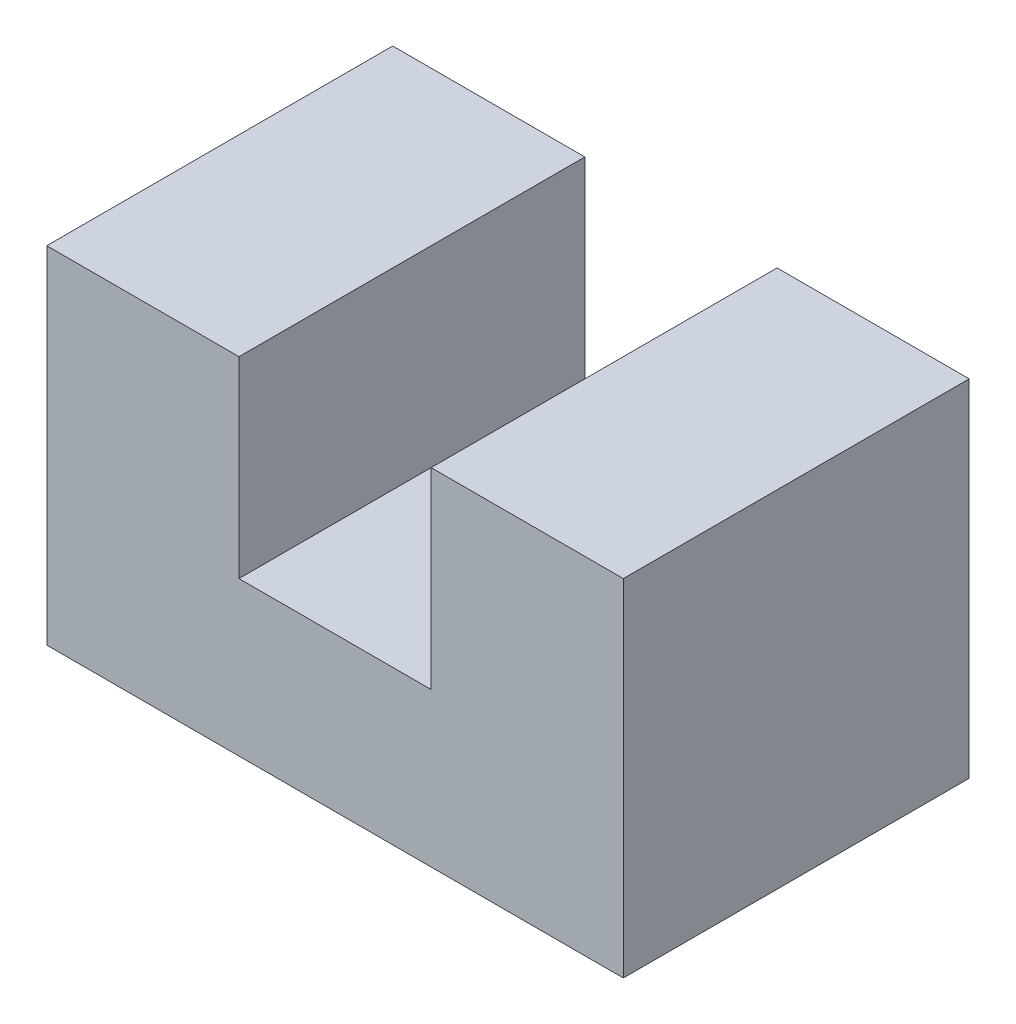
SolidWorks part; units mm, degrees
ref_plane "Front Plane" through (0, 0, 0) normal (0, 0, 1) x (1, 0, 0)
ref_plane "Top Plane" through (0, 0, 0) normal (0, 1, 0) x (1, 0, 0)
ref_plane "Right Plane" through (0, 0, 0) normal (1, 0, 0) x (0, 0, -1)
sketch "Esquisse1" plane through (0, 0, 0) normal (0, 0, 1) x (1, 0, 0)
  line L0 (0, 0) -> (100, 0)
  line L1 (100, 0) -> (100, 60)
  line L2 (100, 60) -> (66.6667, 60)
  line L3 (66.6667, 60) -> (66.6667, 26.6667)
  line L4 (66.6667, 26.6667) -> (33.3333, 26.6667)
  line L5 (33.3333, 26.6667) -> (33.3333, 60)
  line L6 (33.3333, 60) -> (0, 60)
  line L7 (0, 60) -> (0, 0)
  dimension "D1" = 100
  dimension "D2" = 60
extrude "Extrusion1" add sketch "Esquisse1" along normal mid plane 60
